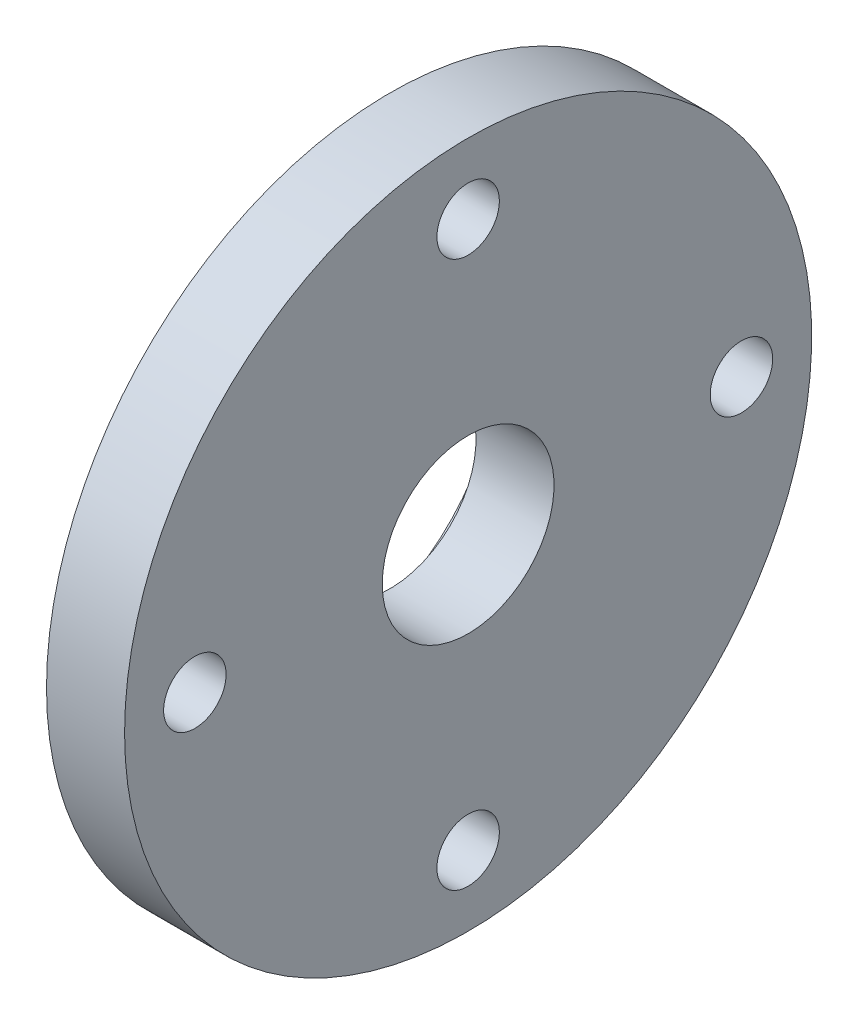
SolidWorks part; units mm, degrees
ref_plane "Front Plane" through (0, 0, 0) normal (0, 0, 1) x (1, 0, 0)
ref_plane "Top Plane" through (0, 0, 0) normal (0, 1, 0) x (1, 0, 0)
ref_plane "Right Plane" through (0, 0, 0) normal (1, 0, 0) x (0, 0, -1)
sketch "Sketch1" plane through (0, 0, 0) normal (0, 0, 1) x (1, 0, 0)
  line L0 (-28.7719, 0) -> (32.5731, 0) construction
  line L1 (-13.6374, 11) -> (-3.6374, 11)
  line L2 (-3.6374, 11) -> (-3.6374, 44)
  line L3 (-3.6374, 44) -> (-13.6374, 44)
  line L4 (-13.6374, 44) -> (-13.6374, 26)
  line L5 (-13.6374, 26) -> (-21.6374, 26)
  line L6 (-21.6374, 26) -> (-21.6374, 22)
  line L7 (-21.6374, 22) -> (-13.6374, 22)
  line L8 (-13.6374, 22) -> (-13.6374, 11)
  point P5 (0, 0)
  dimension "D1" = 10
  dimension "D2" = 18
  dimension "D3" = 22
  dimension "D4" = 88
  dimension "D5" = 52
  dimension "D6" = 44
revolve "Revolve1" add sketch "Sketch1" angle 360 about L0
sketch "Sketch2" plane through (-3.6374, 0, 0) normal (1, 0, 0) x (0, 0, -1)
  circle A0 centre (0, 0) radius 35 construction
  circle A1 centre (0, 35) radius 4
  circle A2 centre (35, 0) radius 4
  circle A3 centre (0, -35) radius 4
  circle A4 centre (-35, 0) radius 4
  point P14 (0, 0)
  dimension "D1" = 4
extrude "Cut-Extrude1" cut sketch "Sketch2" against normal through all
